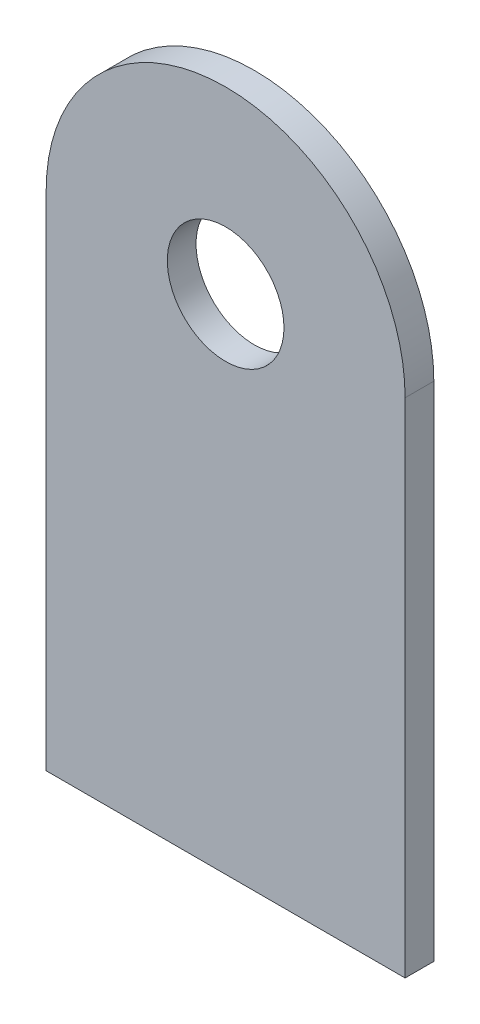
SolidWorks part; units mm, degrees
material "Plain Carbon Steel"
ref_plane "Front Plane" through (0, 0, 0) normal (0, 0, 1) x (1, 0, 0)
ref_plane "Top Plane" through (0, 0, 0) normal (0, 1, 0) x (1, 0, 0)
ref_plane "Right Plane" through (0, 0, 0) normal (1, 0, 0) x (0, 0, -1)
sketch "Sketch2" plane through (0, 0, 0) normal (0, 0, 1) x (1, 0, 0)
  line L1 (0, 0) -> (15.875, 0)
  line L2 (0, 0) -> (0, 22.225)
  line L4 (15.875, 0) -> (15.875, 22.225)
  arc A0 (0, 22.225) -> (15.875, 22.225) centre (7.9375, 22.225) cw
  circle A1 centre (7.9375, 22.225) radius 2.5797
  point P6 (0, 0)
  dimension "D3" = 5.1594
  dimension "D1" = 15.875
  dimension "D2" = 22.225
extrude "Boss-Extrude1" add sketch "Sketch2" along normal blind 1.27 contours A0 L2 L1 L4 A1
